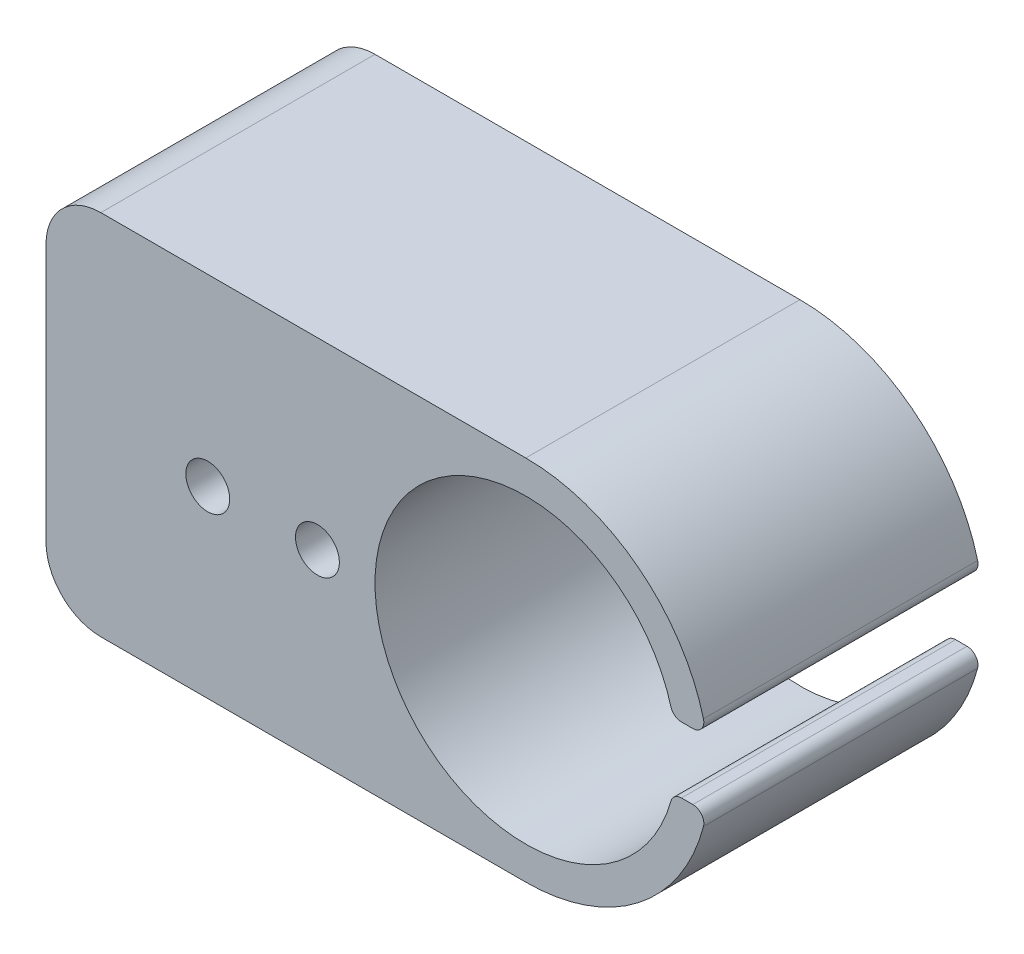
SolidWorks part; units mm, degrees
ref_plane "Plan de face" through (0, 0, 0) normal (0, 0, 1) x (1, 0, 0)
ref_plane "Plan de dessus" through (0, 0, 0) normal (0, 1, 0) x (1, 0, 0)
ref_plane "Plan de droite" through (0, 0, 0) normal (1, 0, 0) x (0, 0, -1)
sketch "Esquisse1" plane through (0, 0, 0) normal (0, 0, 1) x (1, 0, 0)
  line L0 (0, 0) -> (13.75, 0) construction
  line L1 (0, 3) -> (21.7672, 3) construction
  line L2 (0, -3) -> (21.7672, -3) construction
  line L3 (13.4187, 3) -> (16.4792, 3)
  line L4 (16.4792, -3) -> (13.4187, -3)
  line L5 (0, 0) -> (0, 16.75) construction
  line L6 (0, -16.75) -> (-43.75, -16.75)
  line L7 (-43.75, -16.75) -> (-43.75, 16.75)
  line L8 (-43.75, 16.75) -> (0, 16.75)
  circle A0 centre (0, 0) radius 13.75 construction
  arc A1 (13.4187, 3) -> (13.4187, -3) centre (0, 0) ccw
  arc A3 (16.4792, 3) -> (0, 16.75) centre (0, 0) ccw
  arc A4 (16.4792, -3) -> (0, -16.75) centre (0, 0) cw
  circle A5 centre (-29, 0) radius 2
  circle A6 centre (-19, 0) radius 2
  point P18 (-13.75, 0)
  dimension "D1" = 27.5
  dimension "D2" = 6
  dimension "D3" = 30
  dimension "D4" = 3
  dimension "D6" = 4
  dimension "D5" = 10
  dimension "D7" = 19
extrude "Boss.-Extru.1" add sketch "Esquisse1" along normal blind 25
sketch "Esquisse5" plane through (-43.75, 0, 0) normal (-1, 0, 0) x (0, 0, 1)
  line L0 (0, 0) -> (25, 0) construction
  line L2 (12.5, 0) -> (12.5, 16.75) construction
  line L3 (25, 16.75) -> (0, 16.75) construction
  line L4 (25, 16.75) -> (25, -16.75) construction
  circle A0 centre (7.5, 0) radius 2
  circle A1 centre (17.5, 0) radius 2
  dimension "D1" = 4
  dimension "D2" = 10
extrude "Enlèv. mat.-Extru.2" cut sketch "Esquisse5" against normal blind 10
fillet "Congé1" radius 5 2 edges at (-43.75, -16.75, 12.5) (-43.75, 16.75, 12.5)
fillet "Congé2" radius 1 4 edges at (16.4792, -3, 12.5) (16.4792, 3, 12.5) (13.4187, -3, 12.5) (13.4187, 3, 12.5)
